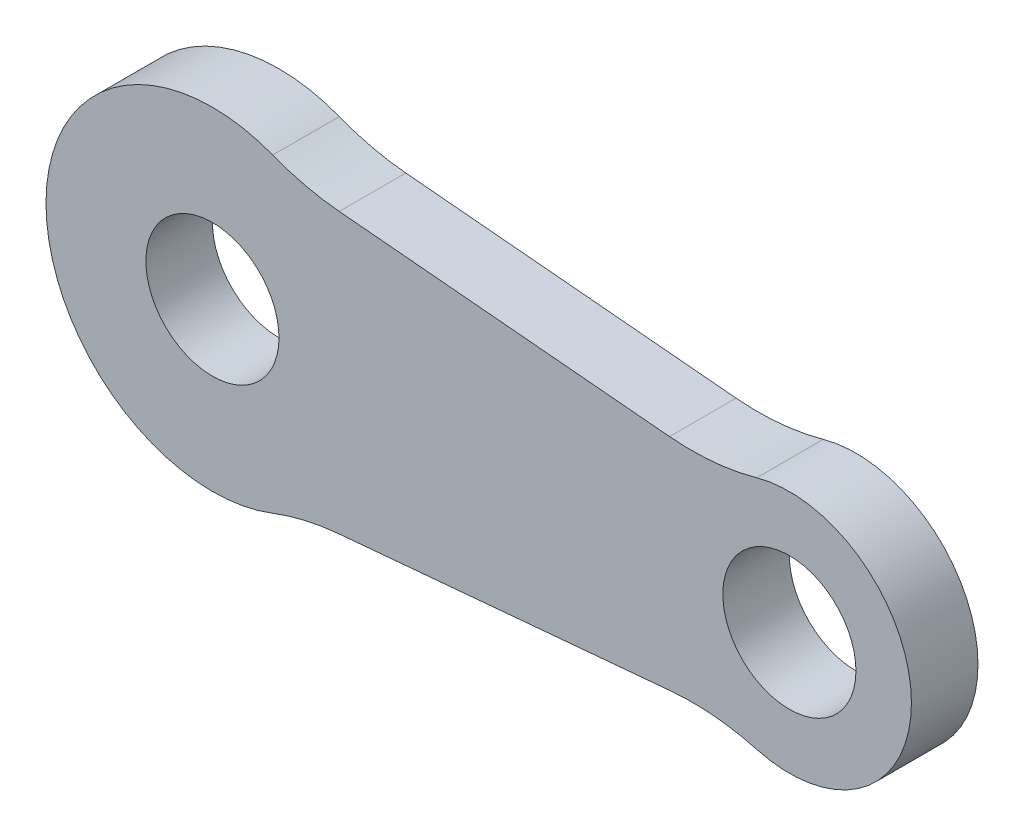
SolidWorks part; units mm, degrees
ref_plane "Front Plane" through (0, 0, 0) normal (0, 0, 1) x (1, 0, 0)
ref_plane "Top Plane" through (0, 0, 0) normal (0, 1, 0) x (1, 0, 0)
ref_plane "Right Plane" through (0, 0, 0) normal (1, 0, 0) x (0, 0, -1)
sketch "Sketch1" plane through (0, 0, 0) normal (0, 0, 1) x (1, 0, 0)
  line L0 (28.5728, 31.4364) -> (102.9917, 24.7179)
  line L1 (28.3456, -31.5276) -> (103.2362, -24.7814)
  circle A0 centre (0, 0) radius 15
  arc A1 (13.5884, 34.9515) -> (13.4919, -34.9888) centre (0, 0) ccw
  circle A2 centre (130, 0) radius 15
  arc A3 (122.7235, -26.5199) -> (122.6456, 26.4984) centre (130, 0) ccw
  arc A4 (102.9917, 24.7179) -> (122.6456, 26.4984) centre (107.9369, 79.4951) ccw
  arc A5 (103.2362, -24.7814) -> (122.7235, -26.5199) centre (108.1706, -79.5596) cw
  arc A6 (28.3456, -31.5276) -> (13.4919, -34.9888) centre (33.2801, -86.3058) ccw
  arc A7 (28.5728, 31.4364) -> (13.5884, 34.9515) centre (33.5181, 86.2136) cw
  dimension "D1" = 130
  dimension "D2" = 30
  dimension "D3" = 30
  dimension "D4" = 75
  dimension "D5" = 55
  dimension "D6" = 27.5
  dimension "D7" = 55
extrude "Boss-Extrude1" add sketch "Sketch1" along normal blind 15 contours A0 | A1 A6 L1 A5 A3 A4 L0 A7 | A2
